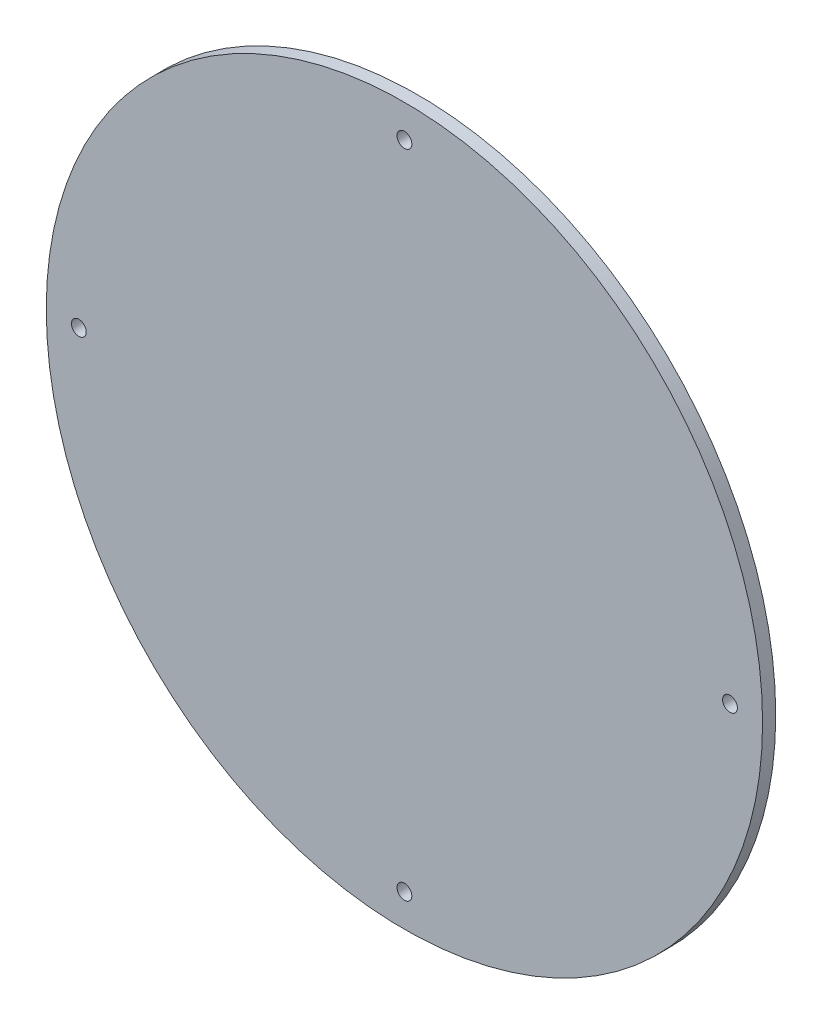
SolidWorks part; units mm, degrees
ref_plane "Front Plane" through (0, 0, 0) normal (0, 0, 1) x (1, 0, 0)
ref_plane "Top Plane" through (0, 0, 0) normal (0, 1, 0) x (1, 0, 0)
ref_plane "Right Plane" through (0, 0, 0) normal (1, 0, 0) x (0, 0, -1)
sketch "Sketch1" plane through (0, 0, 0) normal (0, 0, 1) x (1, 0, 0)
  line L0 (0, 78.5) -> (0, 0) construction
  line L1 (-78.5, 0) -> (-1.5065, 0) construction
  circle A0 centre (0, 0) radius 86.36
  circle A1 centre (0, 78.5) radius 1.7859
  circle A2 centre (78.5, 0) radius 1.7859
  circle A3 centre (0, -78.5) radius 1.7859
  circle A4 centre (-78.5, 0) radius 1.7859
  point P14 (0, 0)
  point P28 (0, 0)
  dimension "D1" = 172.72
  dimension "D2" = 3.5719
  dimension "D3" = 78.5
  dimension "D5" = 78.5
  dimension "D4" = 4
extrude "Boss-Extrude1" add sketch "Sketch1" along normal blind 3.175 contours A0 A4 A3 A2 A1
sketch "Sketch2" plane through (0, 0, 3.175) normal (0, 0, 1) x (1, 0, 0)
  line L0 (2.159, 2.3279) -> (2.159, -2.3279)
  arc A0 (2.159, 2.3279) -> (2.159, -2.3279) centre (0, 0) ccw
  circle A1 centre (0, 0) radius 12.7
  dimension "D1" = 6.35
  dimension "D2" = 25.4
  dimension "D3" = 2.159
